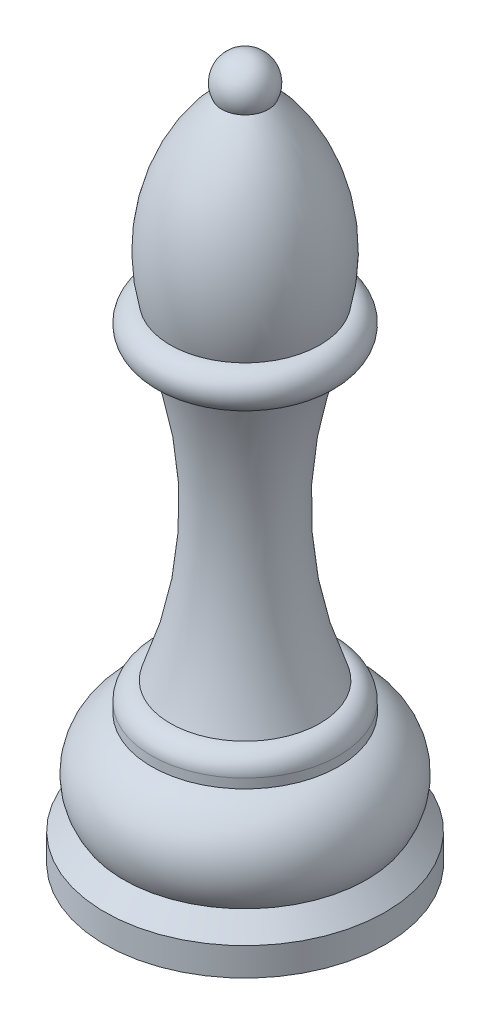
SolidWorks part; units mm, degrees
ref_plane "Front Plane" through (0, 0, 0) normal (0, 0, 1) x (1, 0, 0)
ref_plane "Top Plane" through (0, 0, 0) normal (0, 1, 0) x (1, 0, 0)
ref_plane "Right Plane" through (0, 0, 0) normal (1, 0, 0) x (0, 0, -1)
sketch "Sketch1" plane through (0, 0, 0) normal (0, 0, 1) x (1, 0, 0)
  line L0 (0, -540.3238) -> (0, 26475.8671) construction
  line L1 (0, 0) -> (-15, 0)
  line L2 (-15, 0) -> (-15, 3)
  line L3 (-15, 3) -> (-13, 5)
  line L4 (-10, 13.97) -> (-10, 14.97)
  line L5 (-7.5, 47.99) -> (-8, 47.99)
  line L6 (-10, 49.99) -> (0, 49.99) construction
  line L7 (-2.5, 71.05) -> (0, 71.05)
  line L8 (0, 75.05) -> (0, 0)
  arc A0 (-13, 5) -> (-10, 13.97) centre (-7.9981, 8.3138) cw
  arc A1 (-10, 14.97) -> (-8, 16.97) centre (-8, 14.97) cw
  arc A2 (-8, 16.97) -> (-7.5, 47.99) centre (-49.9864, 33.1608) ccw
  arc A3 (-8, 47.99) -> (-10, 49.99) centre (-8, 49.99) cw
  arc A4 (-10, 49.99) -> (-8, 51.99) centre (-8, 49.99) cw
  arc A5 (-8, 51.99) -> (-2.5, 71.05) centre (11.4363, 56.705) cw
  arc A6 (0, 75.05) -> (-2.5, 71.05) centre (0, 72.2688) ccw
  point P24 (0, 75.05)
  dimension "D6" = 6
  dimension "D9" = 2
  dimension "D13" = 45
  dimension "D14" = 2
  dimension "D19" = 20
  dimension "D1" = 30
  dimension "D2" = 2
  dimension "D3" = 26
  dimension "D4" = 3
  dimension "D5" = 8.97
  dimension "D7" = 20
  dimension "D8" = 1
  dimension "D10" = 16
  dimension "D11" = 15
  dimension "D12" = 31.02
  dimension "D15" = 20
  dimension "D16" = 16
  dimension "D17" = 5
  dimension "D18" = 19.06
  dimension "D20" = 4
revolve "Revolve1" add sketch "Sketch1" angle 360 about L0
